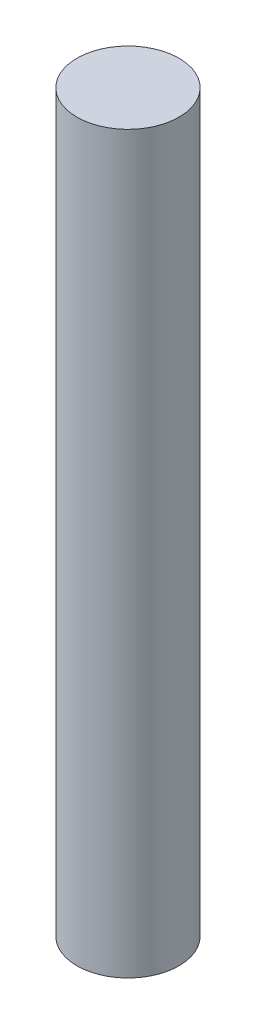
SolidWorks part; units mm, degrees
ref_plane "Front Plane" through (0, 0, 0) normal (0, 0, 1) x (1, 0, 0)
ref_plane "Top Plane" through (0, 0, 0) normal (0, 1, 0) x (1, 0, 0)
ref_plane "Right Plane" through (0, 0, 0) normal (1, 0, 0) x (0, 0, -1)
sketch "Sketch1" plane through (0, 0, 0) normal (0, 1, 0) x (1, 0, 0)
  circle A0 centre (0, 0) radius 1.5875
  dimension "D1" = 3.175
extrude "Boss-Extrude1" add sketch "Sketch1" along normal blind 22.86
